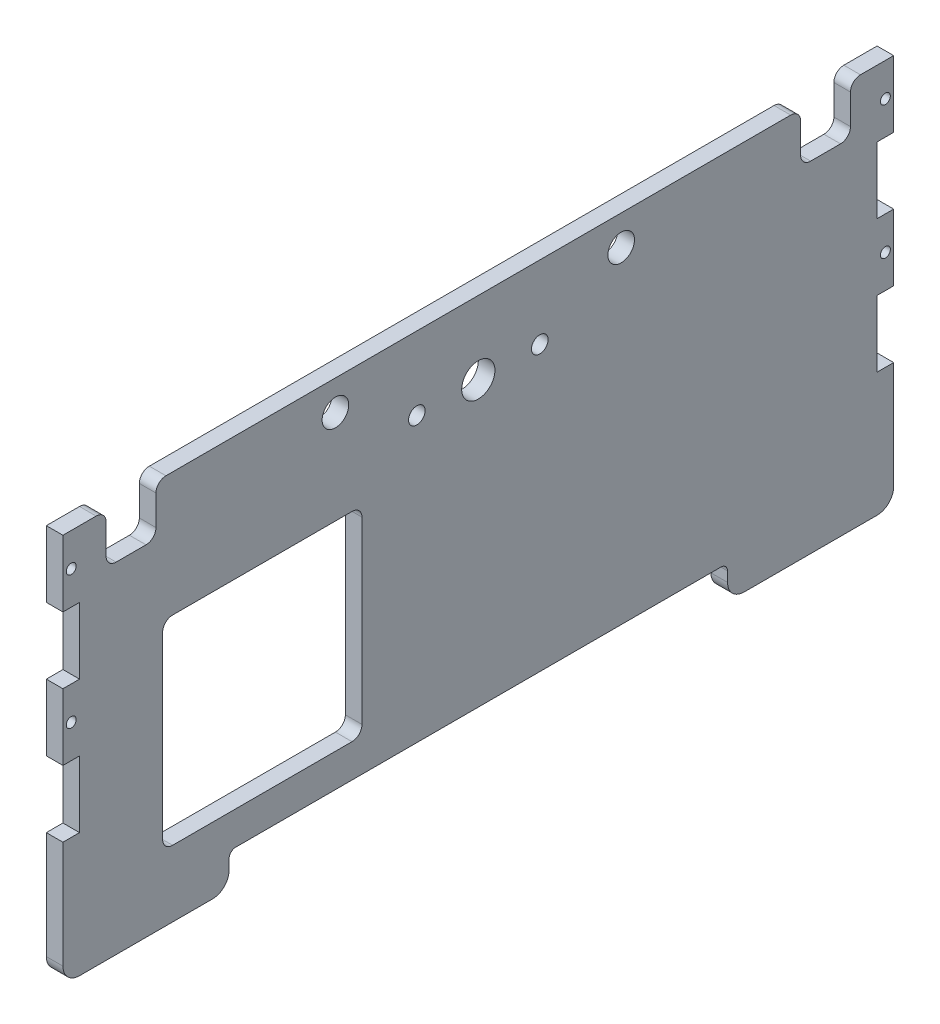
SolidWorks part; units mm, degrees
ref_plane "前视基准面" through (0, 0, 0) normal (0, 0, 1) x (1, 0, 0)
ref_plane "上视基准面" through (0, 0, 0) normal (0, 1, 0) x (1, 0, 0)
ref_plane "右视基准面" through (0, 0, 0) normal (1, 0, 0) x (0, 0, -1)
sketch "草图1" plane through (0, 0, 0) normal (1, 0, 0) x (0, 0, -1)
  line L0 (-84.3455, -47.1906) -> (-84.3455, -44.1906)
  line L1 (-129.3455, -52.1906) -> (-89.3455, -52.1906)
  line L2 (-134.3455, -47.1906) -> (-134.3455, -14.8906)
  line L3 (-134.3455, 65.1094) -> (-124.3455, 65.1094)
  line L4 (115.6545, -47.1906) -> (115.6545, -14.8906)
  line L5 (-82.3455, -42.1906) -> (63.6545, -42.1906)
  line L6 (65.6545, -44.1906) -> (65.6545, -47.1906)
  line L7 (-129.3455, 86.5384) -> (-129.3455, -47.9397) construction
  line L8 (110.6545, 78.4519) -> (110.6545, -47.9397) construction
  line L9 (70.6545, -52.1906) -> (110.6545, -52.1906)
  line L10 (-134.3455, 45.1094) -> (-129.3455, 45.1094)
  line L11 (-129.3455, 45.1094) -> (-129.3455, 25.1094)
  line L12 (-129.3455, 25.1094) -> (-134.3455, 25.1094)
  line L13 (-134.3455, 5.1094) -> (-129.3455, 5.1094)
  line L14 (-129.3455, 5.1094) -> (-129.3455, -14.8906)
  line L15 (-129.3455, -14.8906) -> (-134.3455, -14.8906)
  line L16 (110.6545, 45.1094) -> (115.6545, 45.1094)
  line L17 (-9.3455, 112.2005) -> (-9.3455, -64.6842) construction
  line L18 (115.6545, 25.1094) -> (110.6545, 25.1094)
  line L19 (110.6545, 25.1094) -> (110.6545, 45.1094)
  line L20 (-134.3455, 45.1094) -> (-134.3455, 65.1094)
  line L21 (110.6545, 5.1094) -> (115.6545, 5.1094)
  line L22 (110.6545, 5.1094) -> (110.6545, -14.8906)
  line L23 (110.6545, -14.8906) -> (115.6545, -14.8906)
  line L24 (115.6545, 45.1094) -> (115.6545, 65.1094)
  line L25 (-134.3455, 5.1094) -> (-134.3455, 25.1094)
  line L26 (115.6545, 5.1094) -> (115.6545, 25.1094)
  line L27 (95.1545, 114.7672) -> (95.1545, -69.3365) construction
  line L28 (-113.8455, 117.5092) -> (-113.8455, 65.1094) construction
  line L29 (105.6545, 65.1094) -> (115.6545, 65.1094)
  line L30 (-103.3455, 65.1094) -> (84.6545, 65.1094)
  line L31 (102.6545, 62.1094) -> (102.6545, 53.1094)
  line L32 (99.6545, 50.1094) -> (90.6545, 50.1094)
  line L33 (87.6545, 62.1094) -> (87.6545, 53.1094)
  line L35 (-106.3455, 62.1094) -> (-106.3455, 53.1094)
  line L36 (-109.3455, 50.1094) -> (-118.3455, 50.1094)
  line L37 (-121.3455, 62.1094) -> (-121.3455, 53.1094)
  line L38 (-113.8455, 50.1094) -> (-113.8455, -73.2536) construction
  line L40 (-101.3455, -32.1906) -> (-47.3455, -32.1906)
  line L41 (-104.3455, -29.1906) -> (-104.3455, 24.8094)
  line L42 (-101.3455, 27.8094) -> (-47.3455, 27.8094)
  line L43 (-44.3455, -29.1906) -> (-44.3455, 24.8094)
  circle A0 centre (33.6545, 56.1094) radius 4
  circle A1 centre (-52.3455, 56.1094) radius 4
  circle A2 centre (-9.3455, 43.1094) radius 5
  circle A3 centre (9.1545, 43.1094) radius 2.5
  circle A4 centre (-27.8455, 43.1094) radius 2.5
  arc A5 (-106.3455, 53.1094) -> (-109.3455, 50.1094) centre (-109.3455, 53.1094) cw
  arc A6 (-118.3455, 50.1094) -> (-121.3455, 53.1094) centre (-118.3455, 53.1094) cw
  arc A7 (-129.3455, -52.1906) -> (-134.3455, -47.1906) centre (-129.3455, -47.1906) cw
  arc A8 (-84.3455, -47.1906) -> (-89.3455, -52.1906) centre (-89.3455, -47.1906) cw
  arc A9 (110.6545, -52.1906) -> (115.6545, -47.1906) centre (110.6545, -47.1906) ccw
  arc A10 (65.6545, -47.1906) -> (70.6545, -52.1906) centre (70.6545, -47.1906) ccw
  arc A11 (-84.3455, -44.1906) -> (-82.3455, -42.1906) centre (-82.3455, -44.1906) cw
  arc A12 (63.6545, -42.1906) -> (65.6545, -44.1906) centre (63.6545, -44.1906) cw
  arc A13 (-124.3455, 65.1094) -> (-121.3455, 62.1094) centre (-124.3455, 62.1094) cw
  arc A14 (-103.3455, 65.1094) -> (-106.3455, 62.1094) centre (-103.3455, 62.1094) ccw
  arc A15 (84.6545, 65.1094) -> (87.6545, 62.1094) centre (84.6545, 62.1094) cw
  arc A16 (105.6545, 65.1094) -> (102.6545, 62.1094) centre (105.6545, 62.1094) ccw
  arc A17 (102.6545, 53.1094) -> (99.6545, 50.1094) centre (99.6545, 53.1094) cw
  arc A18 (90.6545, 50.1094) -> (87.6545, 53.1094) centre (90.6545, 53.1094) cw
  circle A19 centre (113.1545, 55.1094) radius 1.5
  circle A20 centre (-131.8455, 55.1094) radius 1.5
  circle A21 centre (-131.8455, 15.1094) radius 1.5
  circle A22 centre (113.1545, 15.1094) radius 1.5
  arc A23 (-47.3455, -32.1906) -> (-44.3455, -29.1906) centre (-47.3455, -29.1906) ccw
  arc A24 (-101.3455, -32.1906) -> (-104.3455, -29.1906) centre (-101.3455, -29.1906) cw
  arc A25 (-104.3455, 24.8094) -> (-101.3455, 27.8094) centre (-101.3455, 24.8094) cw
  arc A26 (-47.3455, 27.8094) -> (-44.3455, 24.8094) centre (-47.3455, 24.8094) cw
  point P68 (-106.3455, 50.1094)
  point P71 (-121.3455, 50.1094)
  point P76 (-106.3455, 65.1094)
  point P79 (87.6545, 65.1094)
  point P82 (102.6545, 65.1094)
  point P85 (102.6545, 50.1094)
  point P88 (87.6545, 50.1094)
  point P97 (-88.2709, -8.9062)
  point P104 (-44.3455, -32.1906)
  point P109 (-104.3455, 27.8094)
  point P112 (-44.3455, 27.8094)
  dimension "D15" = 8
  dimension "D16" = 8
  dimension "D17" = 5
  dimension "D24" = 10
  dimension "D25" = 18.5
  dimension "D26" = 18.5
  dimension "D27" = 22
  dimension "D34" = 5
  dimension "D35" = 2
  dimension "D20" = 5
  dimension "D40" = 3
  dimension "D41" = 10
  dimension "D45" = 3
  dimension "D46" = 3
  dimension "D52" = 10
  dimension "D56" = 3
  dimension "D1" = 5
  dimension "D2" = 5
  dimension "D3" = 10
  dimension "D4" = 250
  dimension "D5" = 50
  dimension "D6" = 50
  dimension "D7" = 20
  dimension "D8" = 20
  dimension "D9" = 20
  dimension "D10" = 20
  dimension "D11" = 20
  dimension "D12" = 20
  dimension "D13" = 20
  dimension "D14" = 20
  dimension "D18" = 9
  dimension "D19" = 9
  dimension "D21" = 125
  dimension "D22" = 43
  dimension "D23" = 43
  dimension "D28" = 22
  dimension "D29" = 22
  dimension "D30" = 209
  dimension "D31" = 20.5
  dimension "D32" = 15
  dimension "D33" = 15
  dimension "D36" = 15
  dimension "D37" = 15
  dimension "D38" = 7.5
  dimension "D39" = 7.5
  dimension "D42" = 2.5
  dimension "D43" = 10
  dimension "D44" = 2.5
  dimension "D47" = 10
  dimension "D48" = 10
  dimension "D49" = 2.5
  dimension "D50" = 2.5
  dimension "D51" = 60
  dimension "D53" = 60
  dimension "D54" = 117.3
  dimension "D55" = 25
extrude "凸台-拉伸1" add sketch "草图1" along normal blind 5
